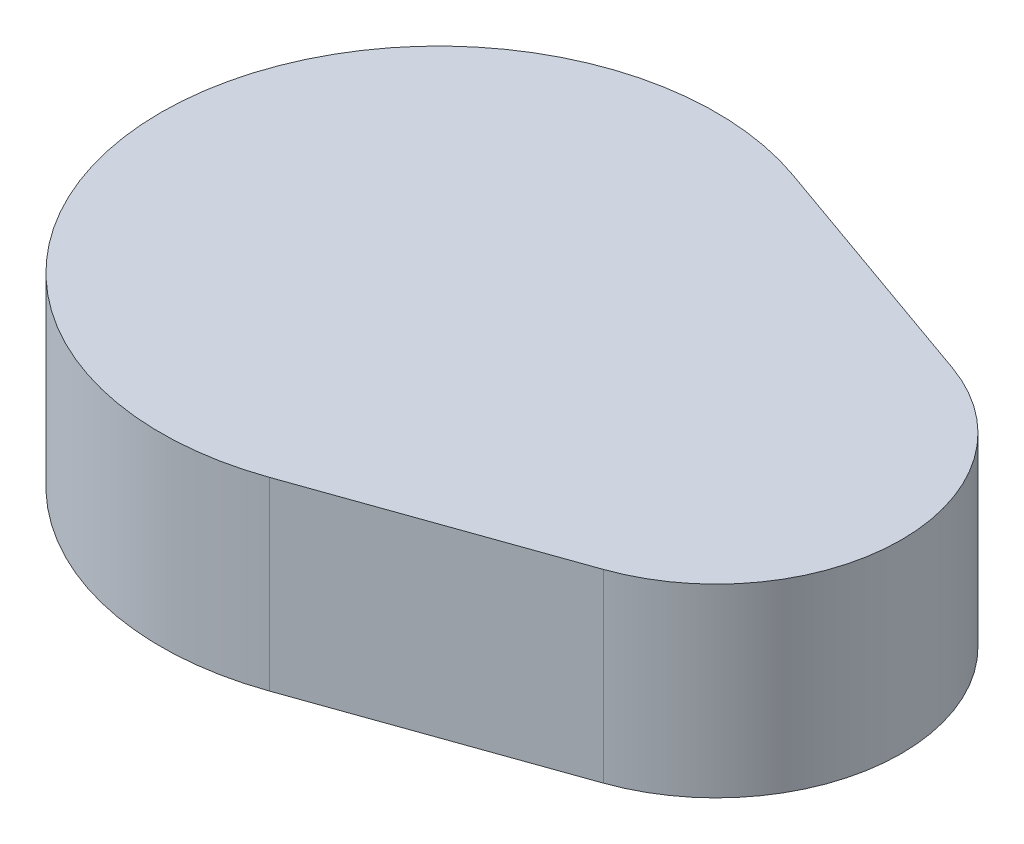
SolidWorks part; units mm, degrees
ref_plane "前视基准面" through (0, 0, 0) normal (0, 0, 1) x (1, 0, 0)
ref_plane "上视基准面" through (0, 0, 0) normal (0, 1, 0) x (1, 0, 0)
ref_plane "右视基准面" through (0, 0, 0) normal (1, 0, 0) x (0, 0, -1)
other "Configuration Table"
sketch "草图1" plane through (0, 0, 0) normal (0, 1, 0) x (1, 0, 0)
  line L0 (5, 14.1421) -> (18.3333, 9.4281)
  line L1 (5, -14.1421) -> (18.3333, -9.4281)
  line L2 (0, 0) -> (15, 0) construction
  arc A0 (5, -14.1421) -> (5, 14.1421) centre (0, 0) cw
  arc A1 (18.3333, 9.4281) -> (18.3333, -9.4281) centre (15, 0) cw
  dimension "D1" = 15
  dimension "D2" = 10
  dimension "D3" = 15
extrude "凸台-拉伸1" add sketch "草图1" along normal blind 10
